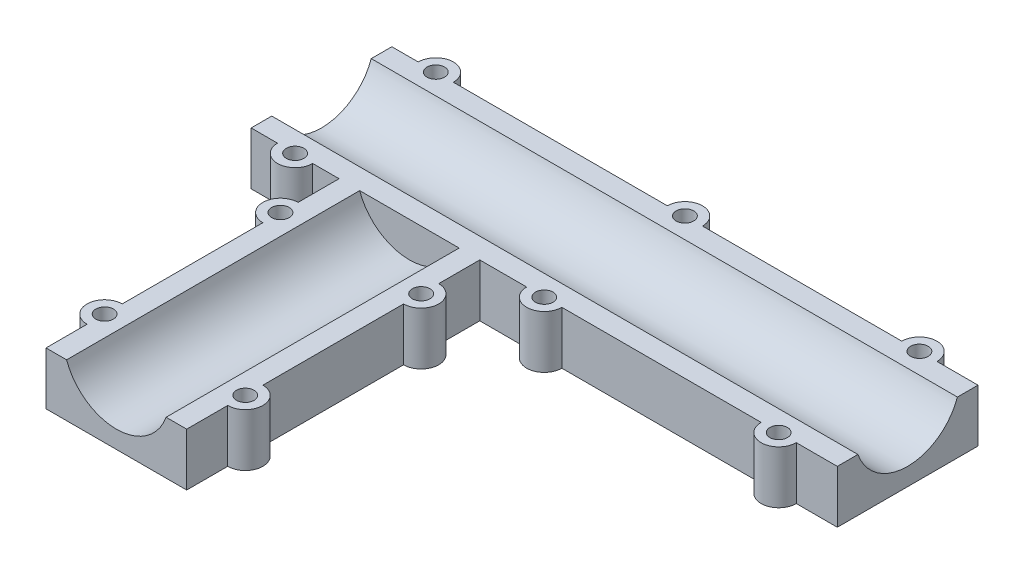
SolidWorks part; units mm, degrees
ref_plane "Front Plane" through (0, 0, 0) normal (0, 0, 1) x (1, 0, 0)
ref_plane "Top Plane" through (0, 0, 0) normal (0, 1, 0) x (1, 0, 0)
ref_plane "Right Plane" through (0, 0, 0) normal (1, 0, 0) x (0, 0, -1)
sketch "Sketch1" plane through (0, 0, 0) normal (1, 0, 0) x (0, 0, -1)
  line L1 (0, 0) -> (24, 0)
  line L2 (0, 0) -> (0, 24)
  line L3 (0, 24) -> (24, 24)
  line L4 (24, 0) -> (24, 24)
  dimension "D1" = 24
  dimension "D2" = 24
extrude "Boss-Extrude1" add sketch "Sketch1" along normal blind 100
sketch "Sketch2" plane through (100, 0, 0) normal (1, 0, 0) x (0, 0, -1)
  line L0 (0, 24) -> (0, 0) construction
  line L2 (0, 0) -> (24, 0) construction
  circle A0 centre (12, 12) radius 9
  dimension "D1" = 18
  dimension "D2" = 12
  dimension "D3" = 12
extrude "Cut-Extrude1" cut sketch "Sketch2" against normal blind 100
sketch "Sketch3" plane through (0, 0, 0) normal (0, 0, 1) x (1, 0, 0)
  line L0 (100, 24) -> (0, 24) construction
  line L1 (15, 24) -> (39, 24)
  line L2 (15, 24) -> (15, 0)
  line L3 (15, 0) -> (39, 0)
  line L4 (39, 24) -> (39, 0)
  line L5 (100, 0) -> (0, 0) construction
  line L6 (0, 24) -> (0, 0) construction
  dimension "D1" = 24
  dimension "D2" = 15
extrude "Boss-Extrude2" add sketch "Sketch3" along normal blind 50
sketch "Sketch4" plane through (0, 0, 50) normal (0, 0, 1) x (1, 0, 0)
  line L0 (15, 24) -> (15, 0) construction
  line L2 (39, 24) -> (15, 24) construction
  circle A0 centre (27, 12) radius 9
  dimension "D1" = 18
  dimension "D2" = 12
  dimension "D3" = 12
extrude "Cut-Extrude2" cut sketch "Sketch4" against normal blind 50
sketch "Sketch5" plane through (0, 24, 0) normal (0, 1, 0) x (1, 0, 0)
  line L0 (100, 0) -> (39, 0) construction
  line L1 (100, 24) -> (0, 24) construction
  line L2 (15, 0) -> (0, 0) construction
  line L3 (15, -50) -> (15, 0) construction
  line L4 (39, -50) -> (39, 0) construction
  line L5 (100, 24) -> (100, 0) construction
  circle A0 centre (90, 0) radius 3
  circle A1 centre (90, 24) radius 3
  circle A2 centre (50, 0) radius 3
  circle A3 centre (50, 24) radius 3
  circle A4 centre (7.5, 0) radius 3
  circle A5 centre (7.5, 24) radius 3
  circle A6 centre (15, -10) radius 3
  circle A7 centre (39, -10) radius 3
  circle A8 centre (15, -40) radius 3
  circle A9 centre (39, -40) radius 3
  dimension "D1" = 6
  dimension "D2" = 6
  dimension "D3" = 6
  dimension "D4" = 6
  dimension "D5" = 6
  dimension "D6" = 6
  dimension "D7" = 6
  dimension "D8" = 6
  dimension "D9" = 6
  dimension "D10" = 6
  dimension "D11" = 30
  dimension "D12" = 10
  dimension "D13" = 30
  dimension "D14" = 10
  dimension "D15" = 7.5
  dimension "D16" = 7.5
  dimension "D17" = 40
  dimension "D18" = 40
  dimension "D19" = 10
  dimension "D20" = 10
extrude "Boss-Extrude3" add sketch "Sketch5" against normal blind 24
sketch "Sketch6" plane through (0, 24, 0) normal (0, 1, 0) x (1, 0, 0)
  circle A2 centre (50, 24) radius 1.5
  circle A3 centre (50, 0) radius 1.5
  circle A4 centre (90, 24) radius 1.5
  circle A5 centre (90, 0) radius 1.5
  circle A6 centre (15, -40) radius 1.5
  circle A7 centre (15, -10) radius 1.5
  circle A8 centre (39, -10) radius 1.5
  circle A9 centre (39, -40) radius 1.5
  circle A10 centre (7.5, 0) radius 1.5
  circle A11 centre (7.5, 24) radius 1.5
  dimension "D1" = 3
  dimension "D2" = 3
  dimension "D3" = 3
  dimension "D4" = 3
  dimension "D5" = 3
  dimension "D6" = 3
  dimension "D7" = 3
  dimension "D8" = 3
  dimension "D9" = 3
  dimension "D10" = 3
extrude "Cut-Extrude3" cut sketch "Sketch6" against normal blind 24
sketch "Sketch7" plane through (100, 0, 0) normal (1, 0, 0) x (0, 0, -1)
  line L6 (27, 0) -> (27, 24) construction
  line L7 (27, 24) -> (-50, 24)
  line L8 (27, 24) -> (27, 9)
  line L9 (27, 9) -> (-50, 9)
  line L10 (-50, 24) -> (-50, 9)
  line L11 (24, 24) -> (0, 24) construction
  line L12 (-50, 0) -> (-50, 24) construction
  dimension "D1" = 0
  dimension "D2" = 0
  dimension "D3" = 0
  dimension "D4" = 15
extrude "Cut-Extrude4" cut sketch "Sketch7" against normal through all both and the other way through all
